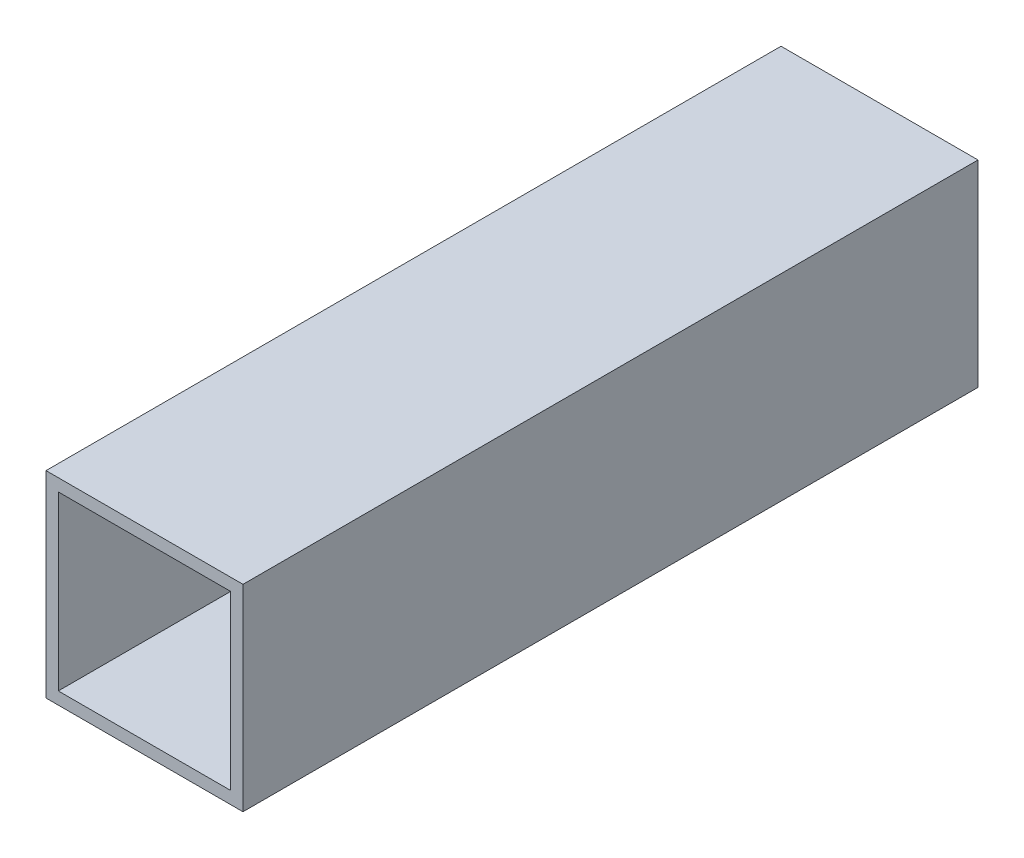
SolidWorks part; units mm, degrees
ref_plane "Front Plane" through (0, 0, 0) normal (0, 0, 1) x (1, 0, 0)
ref_plane "Top Plane" through (0, 0, 0) normal (0, 1, 0) x (1, 0, 0)
ref_plane "Right Plane" through (0, 0, 0) normal (1, 0, 0) x (0, 0, -1)
sketch "Sketch1" plane through (0, 0, 0) normal (0, 0, 1) x (1, 0, 0)
  line L1 (-11.1125, -11.1125) -> (11.1125, -11.1125)
  line L2 (-11.1125, -11.1125) -> (-11.1125, 11.1125)
  line L3 (-11.1125, 11.1125) -> (11.1125, 11.1125)
  line L4 (11.1125, -11.1125) -> (11.1125, 11.1125)
  line L5 (-11.1125, -11.1125) -> (11.1125, 11.1125) construction
  line L6 (-11.1125, 11.1125) -> (11.1125, -11.1125) construction
  line L7 (-12.7, -12.7) -> (12.7, -12.7)
  line L8 (-12.7, -12.7) -> (-12.7, 12.7)
  line L9 (-12.7, 12.7) -> (12.7, 12.7)
  line L10 (12.7, -12.7) -> (12.7, 12.7)
  line L11 (-12.7, -12.7) -> (12.7, 12.7) construction
  line L12 (-12.7, 12.7) -> (12.7, -12.7) construction
  point P0 (0, 0)
  point P6 (0, 0)
  dimension "D1" = 25.4
  dimension "D2" = 1.5875
extrude "Boss-Extrude1" add sketch "Sketch1" along normal blind 94.78
